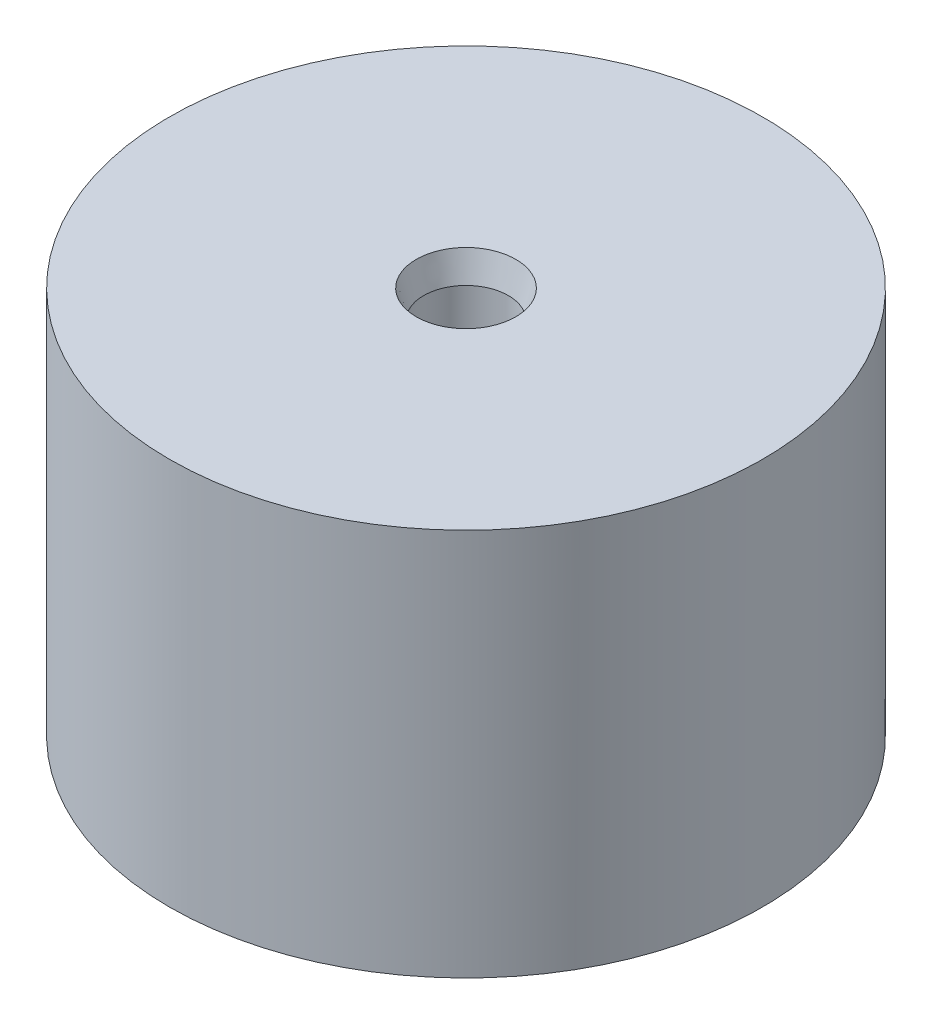
SolidWorks part; units mm, degrees
ref_plane "Front Plane" through (0, 0, 0) normal (0, 0, 1) x (1, 0, 0)
ref_plane "Top Plane" through (0, 0, 0) normal (0, 1, 0) x (1, 0, 0)
ref_plane "Right Plane" through (0, 0, 0) normal (1, 0, 0) x (0, 0, -1)
sketch "Sketch1" plane through (0, 0, 0) normal (0, 0, 1) x (1, 0, 0)
  line L0 (0, 20.7983) -> (0, -18.4168) construction
  line L1 (-12.7012, 0) -> (16.591, 0) construction
  line L2 (-2, 19.6081) -> (-2, -19.1307) construction
  line L3 (-2, 2.5) -> (-2, -2.5)
  line L4 (-2, -2.5) -> (-14, -14.5)
  line L5 (-14, 20.7983) -> (-14, -18.4168) construction
  line L6 (-2, 2.5) -> (-2.35, 3.8062)
  line L7 (-2.35, 3.8062) -> (-14, 3.8062)
  line L8 (-14, 3.8062) -> (-14, -14.5)
  point P10 (-2, 0)
  dimension "D1" = 5
  dimension "D2" = 14
  dimension "D3" = 15
  dimension "D4" = 2
  dimension "D5" = 2.35
  dimension "D6" = 45
revolve "Revolve1" add sketch "Sketch1" angle 360 about L0
